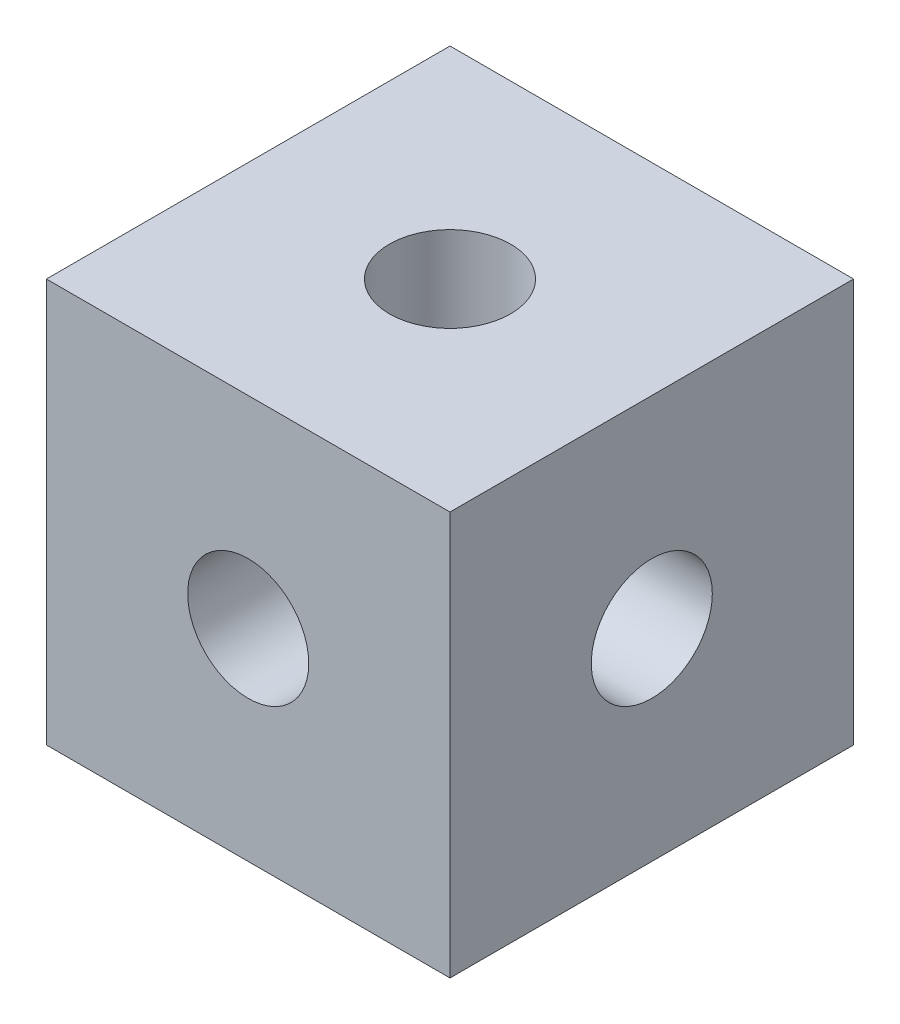
SolidWorks part; units mm, degrees
ref_plane "前视基准面" through (0, 0, 0) normal (0, 0, 1) x (1, 0, 0)
ref_plane "上视基准面" through (0, 0, 0) normal (0, 1, 0) x (1, 0, 0)
ref_plane "右视基准面" through (0, 0, 0) normal (1, 0, 0) x (0, 0, -1)
sketch "草图1" plane through (0, 0, 0) normal (0, 1, 0) x (1, 0, 0)
  line L1 (0, 0) -> (10, 0)
  line L2 (0, 0) -> (0, 10)
  line L3 (0, 10) -> (10, 10)
  line L4 (10, 0) -> (10, 10)
  dimension "D1" = 10
  dimension "D2" = 10
extrude "凸台-拉伸1" add sketch "草图1" along normal blind 10
sketch "草图2" plane through (0, 0, 0) normal (0, 0, 1) x (1, 0, 0)
  line L0 (0, 10) -> (0, 0) construction
  line L1 (0, 0) -> (10, 0) construction
  circle A0 centre (5, 5) radius 1.5
  dimension "D1" = 3
  dimension "D2" = 5
  dimension "D3" = 5
extrude "切除-拉伸1" cut sketch "草图2" against normal through all
sketch "草图3" plane through (10, 0, 0) normal (1, 0, 0) x (0, 0, -1)
  line L0 (0, 10) -> (0, 0) construction
  line L1 (0, 0) -> (10, 0) construction
  circle A0 centre (5, 5) radius 1.5
  dimension "D1" = 3
  dimension "D2" = 5
  dimension "D3" = 5
extrude "切除-拉伸2" cut sketch "草图3" against normal through all
sketch "草图4" plane through (0, 10, 0) normal (0, 1, 0) x (1, 0, 0)
  line L0 (0, 10) -> (0, 0) construction
  line L1 (0, 0) -> (10, 0) construction
  circle A0 centre (5, 5) radius 1.5
  dimension "D1" = 3
  dimension "D2" = 5
  dimension "D3" = 5
extrude "切除-拉伸3" cut sketch "草图4" against normal through all
